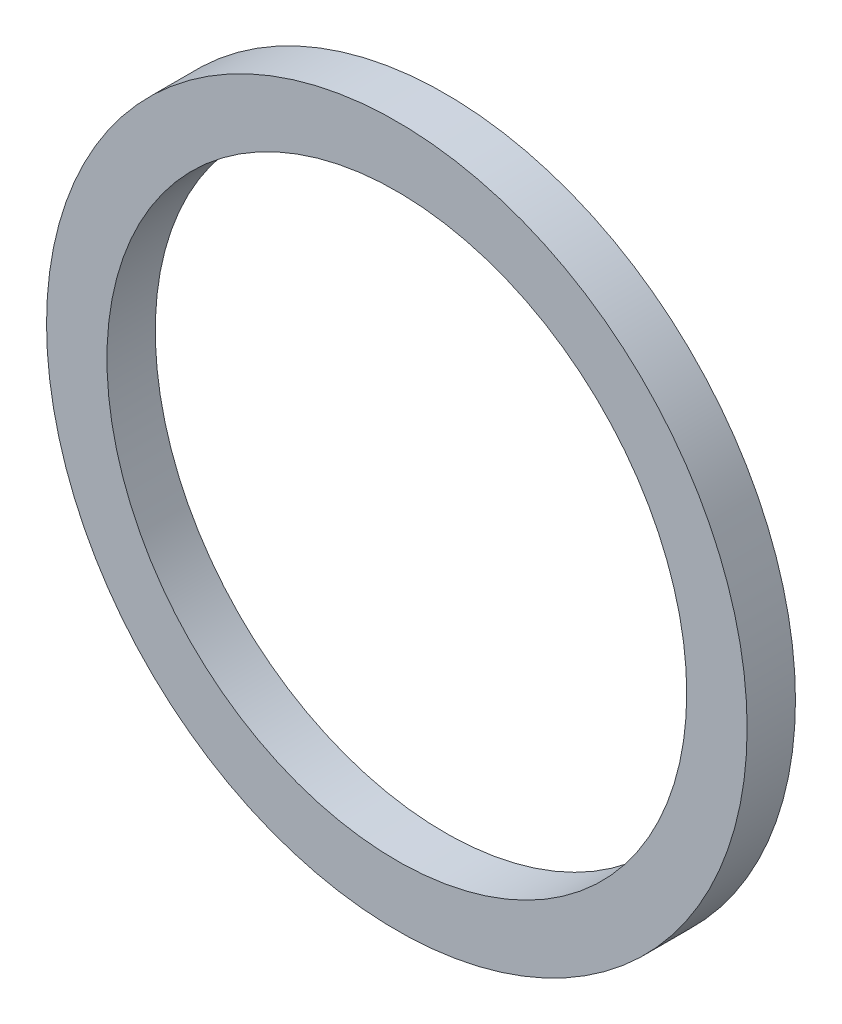
SolidWorks part; units mm, degrees
ref_plane "Front Plane" through (0, 0, 0) normal (0, 0, 1) x (1, 0, 0)
ref_plane "Top Plane" through (0, 0, 0) normal (0, 1, 0) x (1, 0, 0)
ref_plane "Right Plane" through (0, 0, 0) normal (1, 0, 0) x (0, 0, -1)
sketch "Sketch1" plane through (0, 0, 0) normal (0, 0, 1) x (1, 0, 0)
  circle A0 centre (0, 0) radius 72.5
  circle A1 centre (0, 0) radius 60
  dimension "D1" = 145
  dimension "D2" = 120
extrude "Boss-Extrude1" add sketch "Sketch1" along normal blind 10
equation "\"smallPulleyTeeth\"= 15"
equation "\"largePulleyTeeth\"= 40"
equation "\"eighthThick\"= 2.9mm"
equation "\"sixteenthThick\"= 1.7mm"
equation "\"quarterThick\"=5.9mm"
equation "\"OD\"= 145mm"
equation "\"puckAngle\"= 60.5deg"
equation "\"puckDiam\"= 76.5mm"
equation "\"axlePress\"= 5.9mm"
equation "\"press\"= 0.2mm"
equation "\"wheelClear\"= 0.3mm"
equation "\"10-32clear\"= 4.5mm"
equation "\"6-32clear\"= 3.3mm"
equation "\"8-32clear\"= 4.0mm"
equation "\"wheelHeight\"= 24mm"
equation "\"wheelWell\"= 62mm"
equation "\"D1@Sketch1\"=\"OD\""
